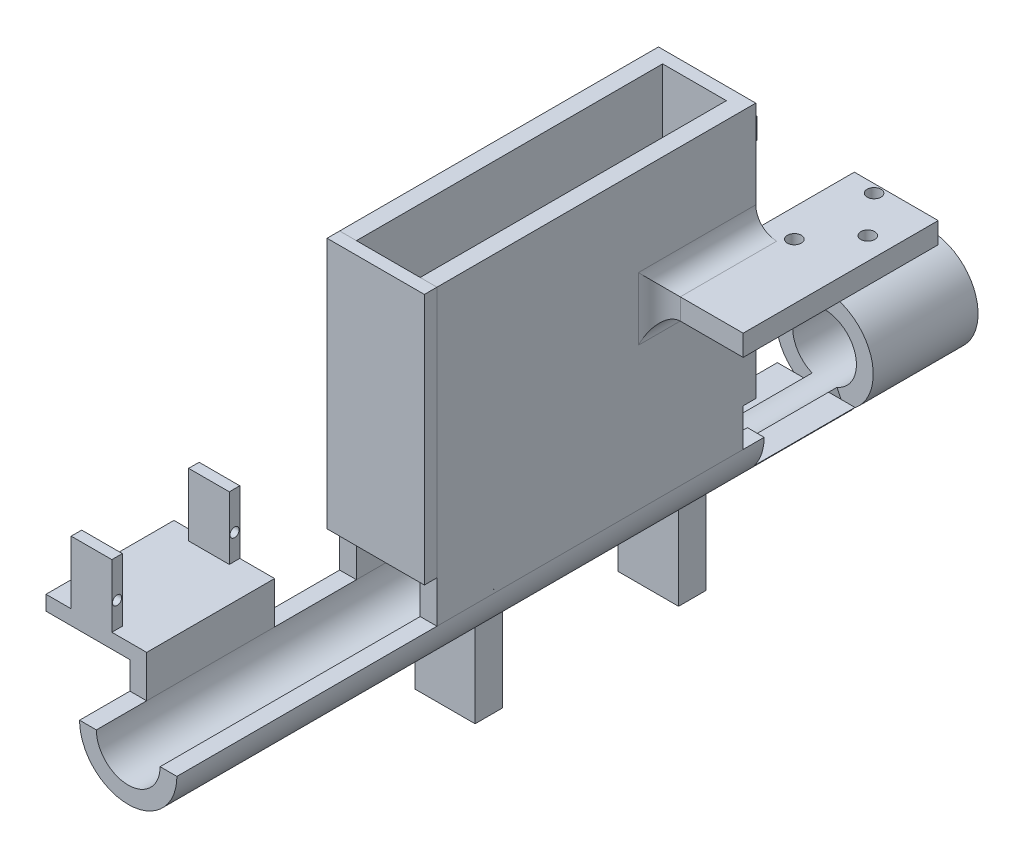
SolidWorks part; units mm, degrees
ref_plane "Front Plane" through (0, 0, 0) normal (0, 0, 1) x (1, 0, 0)
ref_plane "Top Plane" through (0, 0, 0) normal (0, 1, 0) x (1, 0, 0)
ref_plane "Right Plane" through (0, 0, 0) normal (1, 0, 0) x (0, 0, -1)
sketch "Sketch1" plane through (0, 0, 0) normal (0, 0, 1) x (1, 0, 0)
  line L0 (-11.6, 0) -> (-7.6, 0)
  line L1 (7.6, 0) -> (11.6, 0)
  arc A0 (-7.6, 0) -> (7.6, 0) centre (0, 0) ccw
  arc A1 (-11.6, 0) -> (11.6, 0) centre (0, 0) ccw
  dimension "D1" = 7.6
  dimension "D2" = 11.6
extrude "Boss-Extrude1" add sketch "Sketch1" along normal blind 140
sketch "Sketch2" plane through (0, 0, 0) normal (0, 1, 0) x (1, 0, 0)
  line L0 (-11.6, -140) -> (-11.6, 0) construction
  line L1 (-11.6, -78) -> (-7.6, -78)
  line L2 (-11.6, -78) -> (-11.6, -5)
  line L3 (-11.6, -5) -> (-7.6, -5)
  line L4 (-7.6, -78) -> (-7.6, -5)
  line L5 (-7.6, -140) -> (-7.6, 0) construction
  line L6 (7.6, -140) -> (7.6, 0) construction
  line L7 (7.6, -78) -> (11.6, -78)
  line L8 (7.6, -78) -> (7.6, -5)
  line L9 (7.6, -5) -> (11.6, -5)
  line L10 (11.6, -78) -> (11.6, -5)
  line L11 (11.6, -140) -> (11.6, 0) construction
  line L14 (-7.6, -140) -> (-11.6, -140) construction
  line L15 (11.6, -140) -> (7.6, -140) construction
  dimension "D1" = 73
  dimension "D2" = 73
  dimension "D3" = 62
  dimension "D4" = 62
extrude "Boss-Extrude2" add sketch "Sketch2" along normal blind 70
sketch "Sketch5" plane through (0, 0, 5) normal (0, 0, -1) x (-1, 0, 0)
  line L0 (11.6, 70) -> (11.6, 0) construction
  line L1 (-11.6, 70) -> (11.6, 70)
  line L2 (-11.6, 70) -> (-11.6, 9)
  line L3 (-11.6, 9) -> (11.6, 9)
  line L4 (11.6, 70) -> (11.6, 9)
  line L6 (-11.6, 0) -> (-7.6, 0) construction
  dimension "D1" = 9
extrude "Boss-Extrude3" add sketch "Sketch5" along normal blind 3
sketch "Sketch6" plane through (0, 0, 78) normal (0, 0, 1) x (1, 0, 0)
  line L0 (11.6, 70) -> (11.6, 0) construction
  line L1 (-11.6, 70) -> (11.6, 70)
  line L2 (-11.6, 70) -> (-11.6, 10)
  line L3 (-11.6, 10) -> (11.6, 10)
  line L4 (11.6, 70) -> (11.6, 10)
  line L5 (-7.6, 0) -> (-11.6, 0) construction
  dimension "D1" = 10
extrude "Boss-Extrude4" add sketch "Sketch6" along normal blind 3
sketch "Sketch7" plane through (0, 0, 0) normal (0, 1, 0) x (1, 0, 0)
  line L0 (-11.6, -140) -> (-11.6, 0) construction
  line L1 (-11.6, -97.5) -> (-7.6, -97.5)
  line L2 (-11.6, -97.5) -> (-11.6, -128)
  line L3 (-11.6, -128) -> (-7.6, -128)
  line L4 (-7.6, -97.5) -> (-7.6, -128)
  line L5 (-7.6, -140) -> (-7.6, 0) construction
  line L6 (-7.6, -140) -> (-11.6, -140) construction
  dimension "D1" = 30.5
  dimension "D2" = 12
extrude "Boss-Extrude5" add sketch "Sketch7" along normal blind 10
sketch "Sketch8" plane through (-11.6, 0, 0) normal (-1, 0, 0) x (0, 0, 1)
  line L0 (128, 10) -> (128, 0) construction
  line L1 (97.5, 10) -> (128, 10)
  line L2 (97.5, 10) -> (97.5, 6.5)
  line L3 (97.5, 6.5) -> (128, 6.5)
  line L4 (128, 10) -> (128, 6.5)
  dimension "D1" = 3.5
extrude "Boss-Extrude6" add sketch "Sketch8" along normal blind 20
sketch "Sketch10" plane through (0, 10, 0) normal (0, 1, 0) x (1, 0, 0)
  line L1 (-25.6, -125.5) -> (-15.9, -125.5)
  line L2 (-25.6, -125.5) -> (-25.6, -128)
  line L3 (-25.6, -128) -> (-15.9, -128)
  line L4 (-15.9, -125.5) -> (-15.9, -128)
  line L5 (-31.6, -128) -> (-7.6, -128) construction
  line L6 (-7.6, -128) -> (-7.6, -97.5) construction
  line L7 (-25.6, -97.5) -> (-15.9, -97.5)
  line L8 (-25.6, -97.5) -> (-25.6, -100)
  line L9 (-25.6, -100) -> (-15.9, -100)
  line L10 (-15.9, -97.5) -> (-15.9, -100)
  line L12 (-31.6, -128) -> (-31.6, -97.5) construction
  line L13 (-7.6, -97.5) -> (-31.6, -97.5) construction
  dimension "D1" = 2.5
  dimension "D2" = 2.5
  dimension "D3" = 8.3
  dimension "D4" = 8.3
  dimension "D5" = 6
  dimension "D6" = 6
extrude "Boss-Extrude7" add sketch "Sketch10" along normal blind 15
sketch "Sketch11" plane through (-15.9, 0, 0) normal (1, 0, 0) x (0, 0, -1)
  line L0 (-97.5, 25) -> (-97.5, 10) construction
  line L1 (-128, 25) -> (-128, 10) construction
  line L2 (-128, 10) -> (-125.5, 10) construction
  line L3 (-100, 10) -> (-97.5, 10) construction
  circle A0 centre (-98.75, 16) radius 1.1
  circle A1 centre (-126.75, 16) radius 1.1
  dimension "D1" = 2.2
  dimension "D2" = 2.2
  dimension "D3" = 1.25
  dimension "D4" = 1.25
  dimension "D5" = 6
  dimension "D6" = 6
extrude "Cut-Extrude1" cut sketch "Sketch11" against normal blind 7
sketch "Sketch12" plane through (0, 0, 0) normal (0, 0, -1) x (-1, 0, 0)
  line L0 (-9.2499, -7) -> (-2.9597, -7)
  line L1 (2.9597, -7) -> (9.2499, -7)
  arc A0 (-2.9597, -7) -> (2.9597, -7) centre (0, 0) ccw
  arc A1 (-7.6, 0) -> (7.6, 0) centre (0, 0) ccw construction
  arc A3 (-11.6, 0) -> (11.6, 0) centre (0, 0) ccw construction
  arc A4 (-9.2499, -7) -> (9.2499, -7) centre (0, 0) ccw
  dimension "D1" = 7
extrude "Boss-Extrude8" add sketch "Sketch12" along normal blind 24
ref_plane "Plane1" through (0, -11.6, 0) normal (0, -1, 0) x (-1, 0, 0)
sketch "Sketch28" plane through (11.6, 0, 0) normal (1, 0, 0) x (0, 0, -1)
  line L0 (-5, 70) -> (-5, 0) construction
  line L1 (-5, 39) -> (-25, 39)
  line L2 (-5, 39) -> (-5, 44)
  line L3 (-5, 44) -> (-25, 44)
  line L4 (-25, 39) -> (-25, 44)
  line L5 (-78, 0) -> (-5, 0) construction
  dimension "D1" = 20
  dimension "D2" = 5
  dimension "D3" = 39
extrude "Boss-Extrude17" add sketch "Sketch28" along normal blind 20
sketch "Sketch29" plane through (0, 0, 5) normal (0, 0, -1) x (-1, 0, 0)
  line L1 (-31.6, 44) -> (-11.6, 44)
  line L2 (-31.6, 44) -> (-31.6, 39)
  line L3 (-31.6, 39) -> (-11.6, 39)
  line L4 (-11.6, 44) -> (-11.6, 39)
extrude "Boss-Extrude18" add sketch "Sketch29" along normal blind 26.5
fillet "Fillet1" radius 5 3 edges at (11.6, 44, 13.5) (11.6, 41.5, 25) (11.6, 39, 13.5)
sketch "Sketch33" plane through (-11.6, 0, 0) normal (-1, 0, 0) x (0, 0, 1)
  line L0 (5, 70) -> (5, 0) construction
  line L1 (5, 44) -> (25, 44)
  line L2 (5, 44) -> (5, 39)
  line L3 (5, 39) -> (25, 39)
  line L4 (25, 44) -> (25, 39)
  line L5 (5, 0) -> (78, 0) construction
  dimension "D1" = 39
  dimension "D2" = 5
  dimension "D3" = 20
extrude "Boss-Extrude19" add sketch "Sketch33" along normal blind 20
sketch "Sketch34" plane through (0, 0, 5) normal (0, 0, -1) x (-1, 0, 0)
  line L1 (11.6, 44) -> (31.6, 44)
  line L2 (11.6, 44) -> (11.6, 39)
  line L3 (11.6, 39) -> (31.6, 39)
  line L4 (31.6, 44) -> (31.6, 39)
extrude "Boss-Extrude20" add sketch "Sketch34" along normal blind 26.5
fillet "Fillet3" radius 5 3 edges at (-11.6, 39, 13.5) (-11.6, 41.5, 25) (-11.6, 44, 13.5)
sketch "Sketch32" plane through (0, -11.6, 0) normal (0, -1, 0) x (-1, 0, 0)
  line L1 (-10, -64.5) -> (10, -64.5)
  line L2 (-10, -64.5) -> (-10, -9.5)
  line L3 (-10, -9.5) -> (10, -9.5)
  line L4 (10, -64.5) -> (10, -9.5)
  line L5 (-10, -64.5) -> (10, -9.5) construction
  line L6 (-10, -9.5) -> (10, -64.5) construction
  line L7 (-11.6, -140) -> (11.6, -140) construction
  point P0 (0, -37)
  dimension "D1" = 20
  dimension "D2" = 55
  dimension "D3" = 103
extrude "Cut-Extrude4" cut sketch "Sketch32" against normal blind 2.5
sketch "Sketch35" plane through (0, -9.1, 0) normal (0, -1, 0) x (1, 0, 0)
  line L0 (7.1937, 64.5) -> (7.1937, 9.5) construction
  line L1 (-7.1937, 64.5) -> (7.1937, 64.5)
  line L2 (-7.1937, 64.5) -> (-7.1937, 58)
  line L3 (-7.1937, 58) -> (7.1937, 58)
  line L4 (7.1937, 64.5) -> (7.1937, 58)
  line L6 (-7.1937, 9.5) -> (7.1937, 9.5)
  line L7 (-7.1937, 9.5) -> (-7.1937, 16)
  line L8 (-7.1937, 16) -> (7.1937, 16)
  line L9 (7.1937, 9.5) -> (7.1937, 16)
  dimension "D1" = 6.5
  dimension "D2" = 6.5
extrude "Boss-Extrude21" add sketch "Sketch35" along normal blind 20
sketch "Sketch38" plane through (-7.1937, 0, 0) normal (-1, 0, 0) x (0, 0, 1)
  line L1 (16, -29.1) -> (16, -9.1) construction
  line L2 (9.5, -9.1) -> (64.5, -9.1) construction
  circle A0 centre (12.75, -14.6) radius 2.65
  circle A1 centre (12.75, -23.6) radius 2.65
  dimension "D1" = 5.3
  dimension "D2" = 5.3
  dimension "D3" = 9
  dimension "D4" = 5.5
  dimension "D5" = 3.25
extrude "Cut-Extrude6" cut sketch "Sketch38" against normal blind 10
sketch "Sketch39" plane through (-7.1937, 0, 0) normal (-1, 0, 0) x (0, 0, 1)
  line L1 (58, -29.1) -> (58, -9.1) construction
  line L2 (9.5, -9.1) -> (64.5, -9.1) construction
  circle A0 centre (61.25, -14.6) radius 2.65
  circle A1 centre (61.25, -23.6) radius 2.65
  dimension "D1" = 5.3
  dimension "D2" = 5.3
  dimension "D3" = 9
  dimension "D4" = 5.5
  dimension "D5" = 3.25
extrude "Cut-Extrude7" cut sketch "Sketch39" against normal blind 10
sketch "Sketch41" plane through (0, 0, -24) normal (0, 0, -1) x (-1, 0, 0)
  line L0 (-4.7117, -10.6) -> (-2.9597, -7)
  line L1 (2.9597, -7) -> (4.7117, -10.6)
  line L2 (9.2499, -7) -> (2.9597, -7) construction
  arc A0 (-2.9597, -7) -> (2.9597, -7) centre (0, 0) ccw
  arc A1 (-2.9597, -7) -> (2.9597, -7) centre (0, 0) ccw construction
  arc A2 (-4.7117, -10.6) -> (4.7117, -10.6) centre (0, 0) ccw
  arc A3 (-9.2499, -7) -> (9.2499, -7) centre (0, 0) ccw construction
  arc A4 (-9.2499, -7) -> (9.2499, -7) centre (0, 0) ccw construction
  point P14 (-4.7117, -10.6)
  point P17 (-4.7117, -10.6)
  point P18 (0, 0)
  dimension "D2" = 3.6
  dimension "D1" = 3.6
  dimension "D3" = 4.0037
sketch "Sketch43" plane through (0, 44, 0) normal (0, 1, 0) x (1, 0, 0)
  line L0 (11.6, 21.5) -> (11.6, -2) construction
  line L1 (11.6, 21.5) -> (31.6, 21.5) construction
  circle A0 centre (18.3, 10) radius 2.5 construction
  circle A1 centre (18.3, 10) radius 9.5 construction
  circle A2 centre (18.3, 19.5) radius 1.65
  circle A4 centre (18.3, 10) radius 2.5 construction
  circle A6 centre (18.3, 10) radius 2.5 construction
  circle A7 centre (18.3, 0.5) radius 1.65
  circle A8 centre (18.3, 10) radius 8 construction
  circle A9 centre (26.3, 10) radius 1.65
  dimension "D3" = 5
  dimension "D4" = 19
  dimension "D6" = 3.3
  dimension "D5" = 3.3
  dimension "D7" = 16
  dimension "D8" = 3.3
  dimension "D1" = 6.7
  dimension "D2" = 11.5
extrude "Cut-Extrude8" cut sketch "Sketch43" against normal blind 5
mirror "Mirror1" about plane through (0, 0, 0) normal (1, 0, 0) of "Cut-Extrude8"
extrude "Boss-Extrude22" add sketch "Sketch41" along normal blind 2
sketch "Sketch44" plane through (0, 0, -26) normal (0, 0, -1) x (-1, 0, 0)
  circle A0 centre (0, 0) radius 11.6
  circle A1 centre (0, 0) radius 7.6
  dimension "D1" = 15.2
  dimension "D2" = 23.2
extrude "Boss-Extrude23" add sketch "Sketch44" along normal blind 25
sketch "Sketch45" plane through (0, 44, 0) normal (0, 1, 0) x (1, 0, 0)
  line L0 (-31.6, 21.5) -> (-11.6, 21.5) construction
  line L1 (-11.6, 21.5) -> (-11.6, -2) construction
  circle A0 centre (-18.3, 10) radius 2.5 construction
  dimension "D1" = 5
  dimension "D2" = 11.5
  dimension "D3" = 6.7
